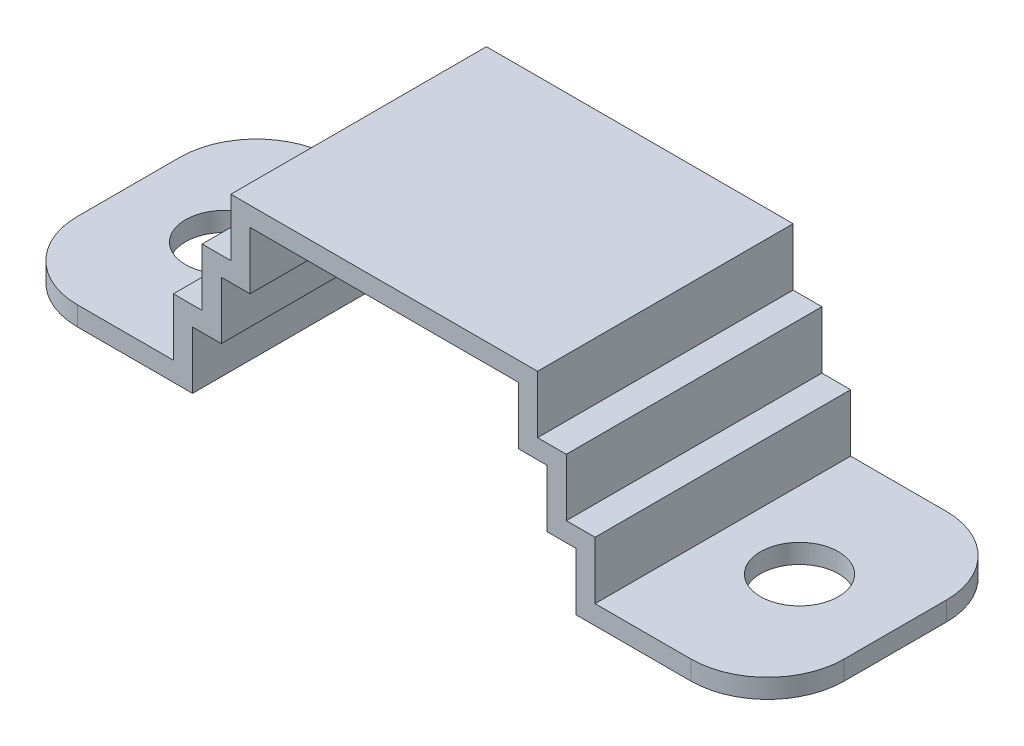
SolidWorks part; units mm, degrees
material "PBT General Purpose"
ref_plane "Front Plane" through (0, 0, 0) normal (0, 0, 1) x (1, 0, 0)
ref_plane "Top Plane" through (0, 0, 0) normal (0, 1, 0) x (1, 0, 0)
ref_plane "Right Plane" through (0, 0, 0) normal (1, 0, 0) x (0, 0, -1)
sketch "Sketch1" plane through (0, 0, 0) normal (0, 0, 1) x (1, 0, 0)
  line L0 (-60, 0) -> (-30, 0)
  line L1 (-30, 0) -> (-30, 9)
  line L2 (-30, 9) -> (-25.5, 9)
  line L3 (-25.5, 9) -> (-25.5, 18)
  line L4 (-25.5, 18) -> (-21, 18)
  line L5 (-21, 18) -> (-21, 27)
  line L6 (-21, 27) -> (0, 27)
  circle A0 centre (0, 0) radius 27.05
  dimension "D1" = 54.1
  dimension "D2" = 9
  dimension "D3" = 30
  dimension "D4" = 4.5
  dimension "D5" = 30
  dimension "D6" = 21
extrude "Extrude-Thin1" add sketch "Sketch1" against normal mid plane 40 thin contours L0 L1 L2 L3 L4 L5 L6
mirror "Mirror1" about plane through (0, 30, -20) normal (-1, 0, 0) of "Extrude-Thin1"
sketch "Sketch4" plane through (0, 3, 0) normal (0, 1, 0) x (1, 0, 0)
  circle A0 centre (-45, 0) radius 6.1
  dimension "D1" = 12.2
  dimension "D2" = 45
extrude "Cut-Extrude3" cut sketch "Sketch4" against normal through all
mirror "Mirror3" about plane through (0, 0, 0) normal (1, 0, 0) of "Cut-Extrude3"
fillet "Fillet1" radius 12 4 edges at (-60, 1.5, -20) (-60, 1.5, 20) (60, 1.5, 20) (60, 1.5, -20)
